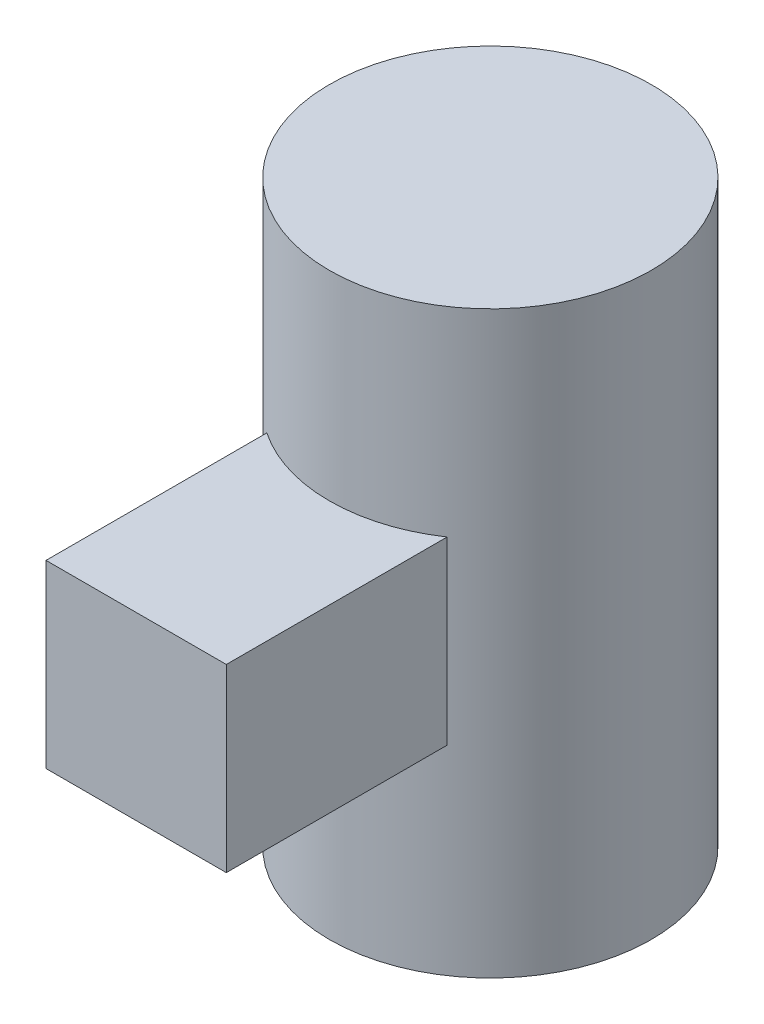
SolidWorks part; units mm, degrees
ref_plane "Front Plane" through (0, 0, 0) normal (0, 0, 1) x (1, 0, 0)
ref_plane "Top Plane" through (0, 0, 0) normal (0, 1, 0) x (1, 0, 0)
ref_plane "Right Plane" through (0, 0, 0) normal (1, 0, 0) x (0, 0, -1)
sketch "Sketch2" plane through (0, 0, 0) normal (0, 1, 0) x (1, 0, 0)
  circle A0 centre (0, 0) radius 31.75
  dimension "D1" = 63.5
extrude "Boss-Extrude1" add sketch "Sketch2" along normal mid plane 114.3
sketch "Sketch3" plane through (0, 0, 0) normal (0, 0, 1) x (1, 0, 0)
  line L1 (-17.78, -17.78) -> (17.78, -17.78)
  line L2 (-17.78, -17.78) -> (-17.78, 17.78)
  line L3 (-17.78, 17.78) -> (17.78, 17.78)
  line L4 (17.78, -17.78) -> (17.78, 17.78)
  line L5 (-17.78, -17.78) -> (17.78, 17.78) construction
  line L6 (-17.78, 17.78) -> (17.78, -17.78) construction
  point P0 (0, 0)
  dimension "D1" = 35.56
  dimension "D2" = 35.56
extrude "Boss-Extrude2" add sketch "Sketch3" along normal blind 69.85
